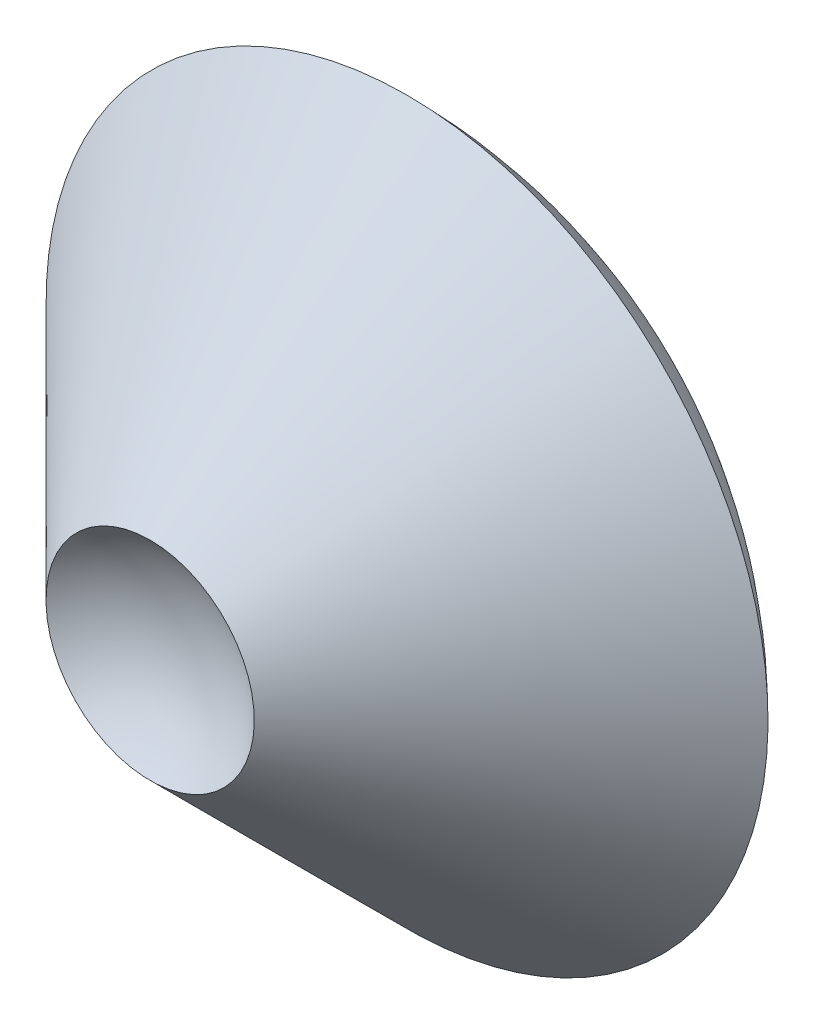
SolidWorks part; units mm, degrees
ref_plane "Front Plane" through (0, 0, 0) normal (0, 0, 1) x (1, 0, 0)
ref_plane "Top Plane" through (0, 0, 0) normal (0, 1, 0) x (1, 0, 0)
ref_plane "Right Plane" through (0, 0, 0) normal (1, 0, 0) x (0, 0, -1)
sketch "Lens Sketch" plane through (0, 0, 0) normal (1, 0, 0) x (0, 0, -1)
  line L0 (-1249.1667, -490) -> (-993.8333, -490) construction
  line L1 (183.8478, 183.8478) -> (53.033, 53.033)
  line L2 (260, 0) -> (75, 0)
  line L3 (53.033, 53.033) -> (0, 0) construction
  line L4 (75, 0) -> (0, 0) construction
  arc A0 (260, 0) -> (183.8478, 183.8478) centre (0, 0) ccw
  arc A1 (75, 0) -> (53.033, 53.033) centre (0, 0) ccw
  dimension "D2" = 260
  dimension "D3" = 75
  dimension "D1" = 45
revolve "Lens Revolution" add sketch "Lens Sketch" angle 360 about L4
